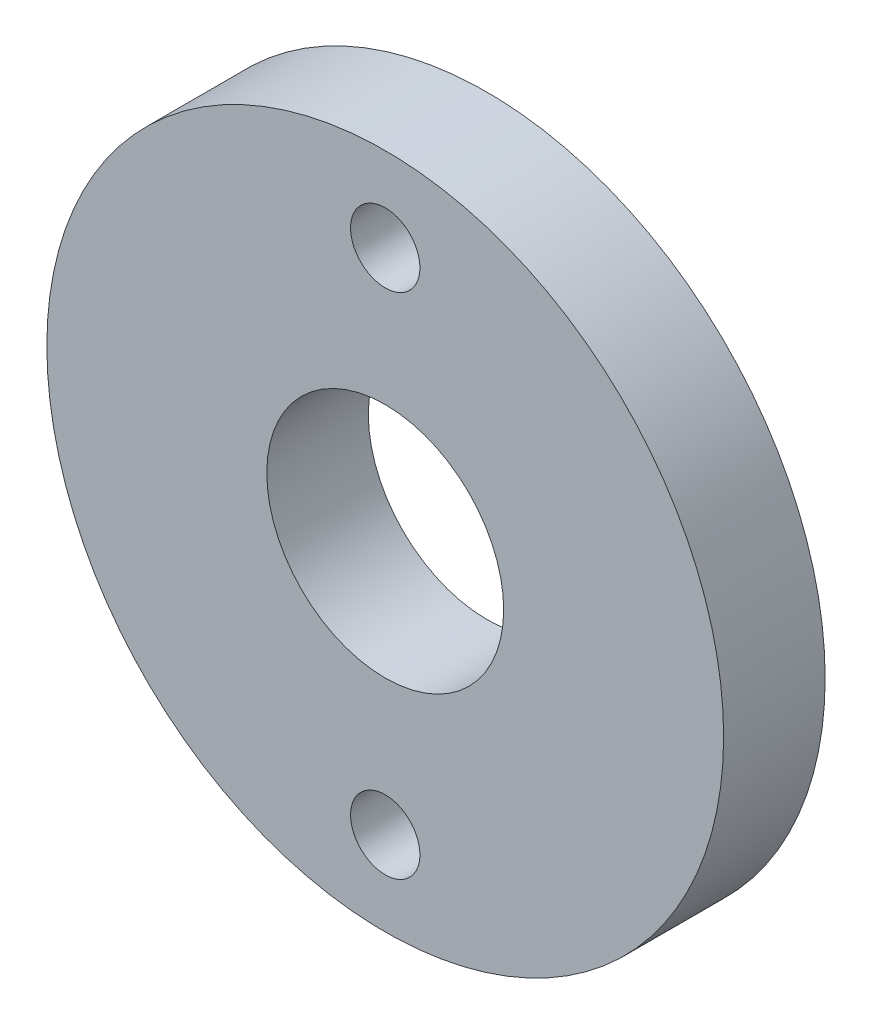
SolidWorks part; units mm, degrees
ref_plane "Alzado" through (0, 0, 0) normal (0, 0, 1) x (1, 0, 0)
ref_plane "Planta" through (0, 0, 0) normal (0, 1, 0) x (1, 0, 0)
ref_plane "Vista lateral" through (0, 0, 0) normal (1, 0, 0) x (0, 0, -1)
sketch "Croquis1" plane through (0, 0, 0) normal (0, 0, 1) x (1, 0, 0)
  circle A0 centre (0, 0) radius 10
  dimension "D1" = 20
extrude "Saliente-Extruir1" add sketch "Croquis1" along normal blind 3
sketch "Croquis2" plane through (0, 0, 3) normal (0, 0, 1) x (1, 0, 0)
  line L0 (0, 10) -> (0, -10) construction
  circle A0 centre (0, 0) radius 10 construction
  circle A1 centre (0, 7.51) radius 1.025
  circle A2 centre (0, -7.51) radius 1.025
  circle A3 centre (0, 0) radius 3.5
  dimension "D1" = 2.05
  dimension "D2" = 2.05
  dimension "D3" = 7.51
  dimension "D4" = 7.51
  dimension "D5" = 7
extrude "Cortar-Extruir1" cut sketch "Croquis2" against normal blind 3
